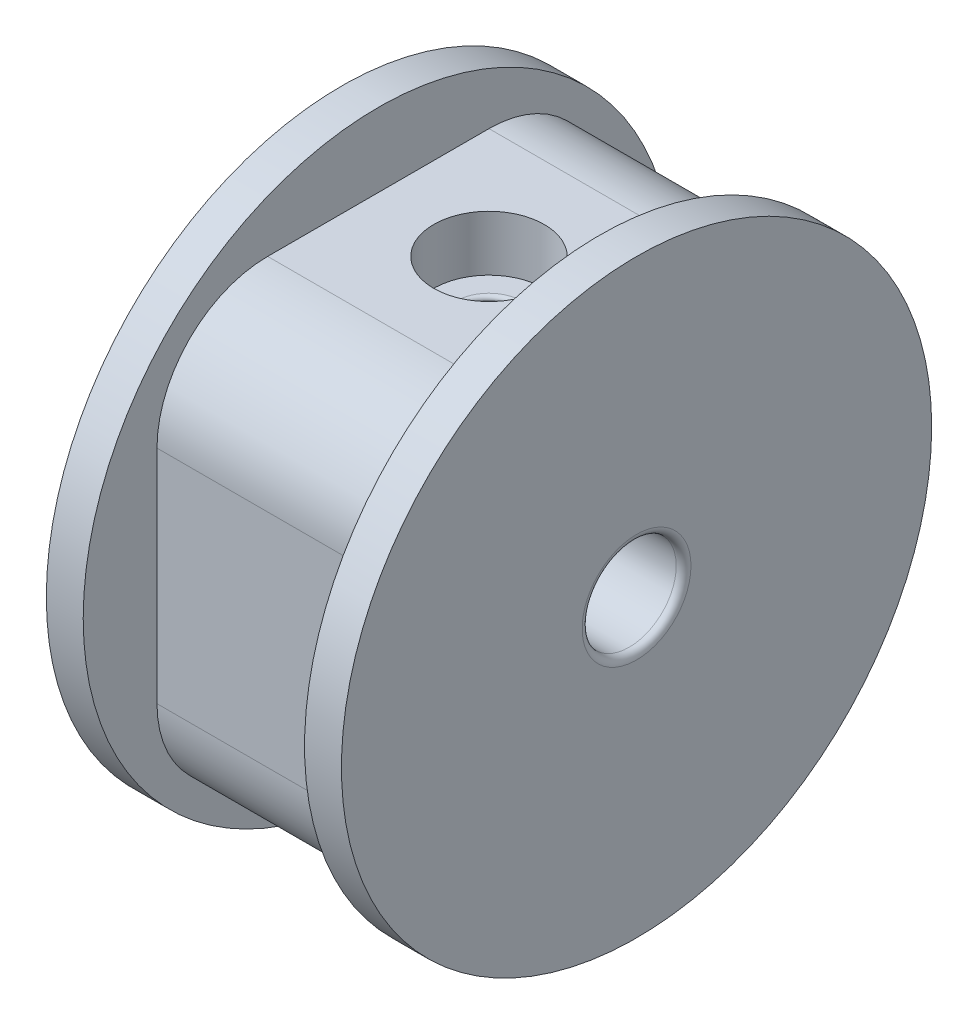
SolidWorks part; units mm, degrees
ref_plane "前视基准面" through (0, 0, 0) normal (0, 0, 1) x (1, 0, 0)
ref_plane "上视基准面" through (0, 0, 0) normal (0, 1, 0) x (1, 0, 0)
ref_plane "右视基准面" through (0, 0, 0) normal (1, 0, 0) x (0, 0, -1)
other "Configuration Table"
sketch "草图1" plane through (0, 0, 0) normal (1, 0, 0) x (0, 0, -1)
  line L1 (0, 0) -> (-24, 0)
  line L2 (0, 0) -> (0, 24)
  line L3 (0, 24) -> (-24, 24)
  line L4 (-24, 0) -> (-24, 24)
  dimension "D1" = 24
  dimension "D2" = 24
extrude "凸台-拉伸1" add sketch "草图1" along normal blind 12
fillet "圆角1" radius 6 4 edges at (6, 0, 0) (6, 0, 24) (6, 24, 0) (6, 24, 24)
sketch "草图3" plane through (0, 24, 0) normal (0, 1, 0) x (1, 0, 0)
  line L0 (6, -6) -> (6, -12) construction
  line L1 (12, -6) -> (0, -6) construction
  circle A0 centre (6, -12) radius 1.6
  dimension "D2" = 3.2
  dimension "D1" = 6
extrude "切除-拉伸1" cut sketch "草图3" against normal blind 9
sketch "草图4" plane through (0, 24, 0) normal (0, 1, 0) x (1, 0, 0)
  circle A0 centre (6, -12) radius 3
  dimension "D1" = 6
extrude "切除-拉伸2" cut sketch "草图4" against normal blind 3
sketch "草图5" plane through (0, 0, 0) normal (-1, 0, 0) x (0, 0, 1)
  line L0 (12, 24) -> (12, 12) construction
  line L1 (6, 24) -> (18, 24) construction
  circle A0 centre (12, 12) radius 1.55
  dimension "D2" = 3.1
  dimension "D1" = 12
extrude "切除-拉伸3" cut sketch "草图5" against normal blind 23
sketch "草图7" plane through (12, 0, 0) normal (1, 0, 0) x (0, 0, -1)
  circle A0 centre (-12, 12) radius 16
  dimension "D1" = 32
extrude "凸台-拉伸2" add sketch "草图7" along normal blind 2
sketch "草图8" plane through (0, 0, 0) normal (-1, 0, 0) x (0, 0, 1)
  circle A0 centre (12, 12) radius 16
extrude "凸台-拉伸3" add sketch "草图8" along normal blind 2
sketch "草图9" plane through (-2, 0, 0) normal (-1, 0, 0) x (0, 0, 1)
  circle A0 centre (12, 12) radius 2.55
  dimension "D1" = 5.1
extrude "切除-拉伸4" cut sketch "草图9" against normal blind 22
fillet "圆角2" radius 0.2 1 edges at (6, 21, 13.6)
fillet "圆角3" radius 0.4 2 edges at (-2, 12, 14.55) (14, 12, 9.45)
